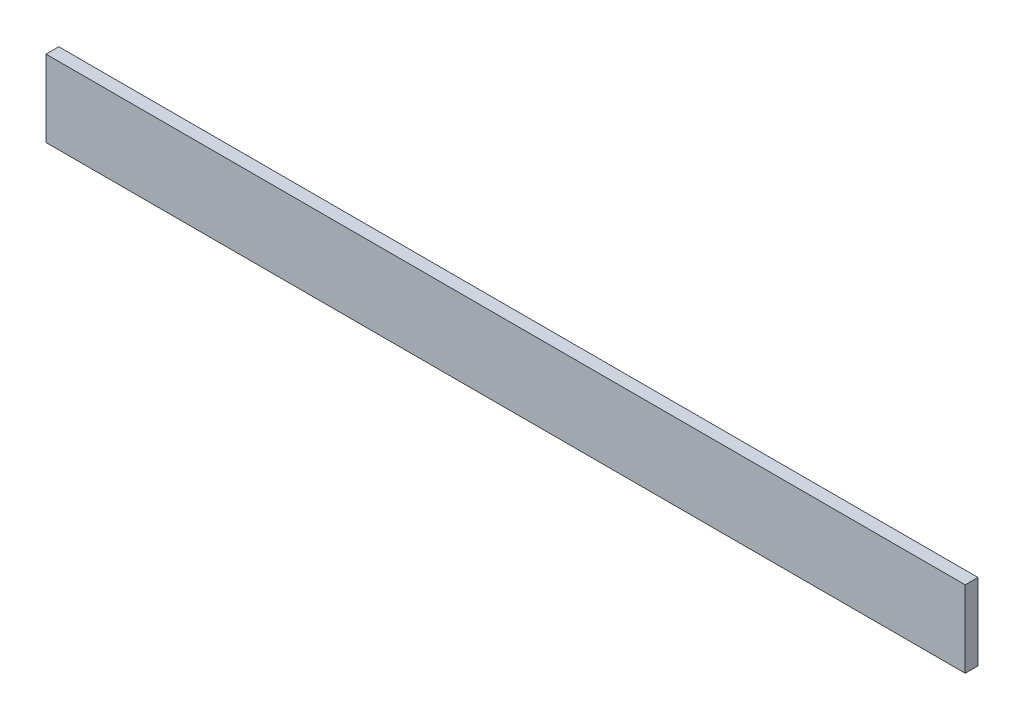
SolidWorks part; units mm, degrees
ref_plane "Front Plane" through (0, 0, 0) normal (0, 0, 1) x (1, 0, 0)
ref_plane "Top Plane" through (0, 0, 0) normal (0, 1, 0) x (1, 0, 0)
ref_plane "Right Plane" through (0, 0, 0) normal (1, 0, 0) x (0, 0, -1)
sketch "Sketch1" plane through (0, 0, 0) normal (1, 0, 0) x (0, 0, -1)
  line L1 (0, 0) -> (50.8, 0)
  line L2 (0, 0) -> (0, 304.8)
  line L3 (0, 304.8) -> (50.8, 304.8)
  line L4 (50.8, 0) -> (50.8, 304.8)
extrude "Boss-Extrude1" add sketch "Sketch1" along normal blind 3657.6
